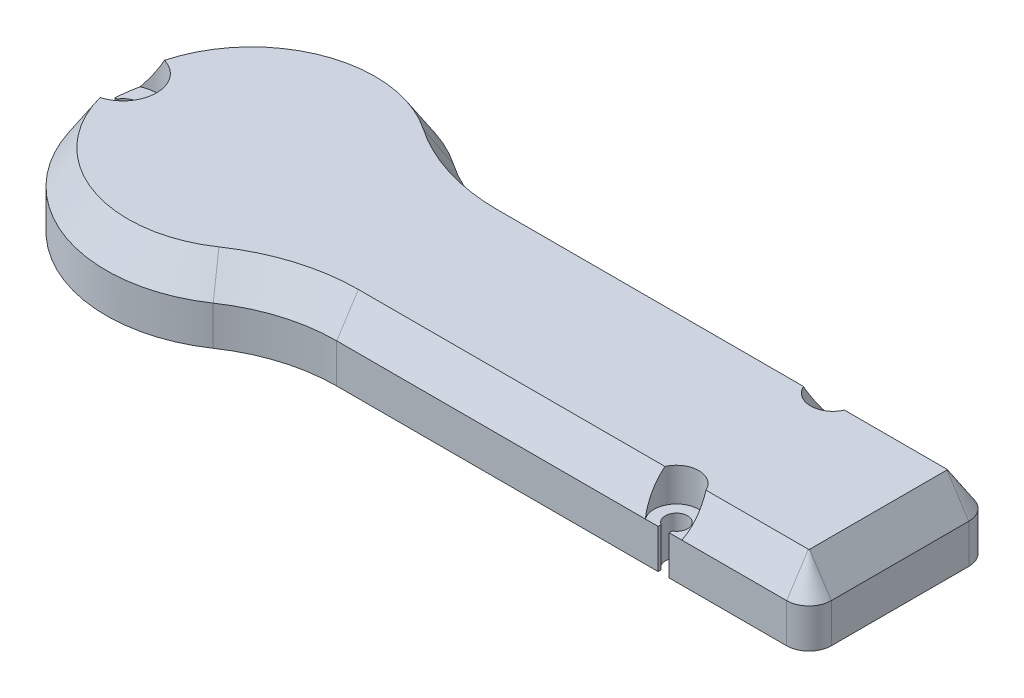
SolidWorks part; units mm, degrees
ref_plane "Front Plane" through (0, 0, 0) normal (0, 0, 1) x (1, 0, 0)
ref_plane "Top Plane" through (0, 0, 0) normal (0, 1, 0) x (1, 0, 0)
ref_plane "Right Plane" through (0, 0, 0) normal (1, 0, 0) x (0, 0, -1)
sketch "Sketch1" plane through (0, 0, 0) normal (0, 1, 0) x (1, 0, 0)
  line L0 (10.1321, 8.145) -> (10.1321, -8.145) construction
  line L1 (0, 0) -> (-11.5, 0) construction
  line L6 (0, 0) -> (45, 0) construction
  line L7 (10.1321, 8.145) -> (44.5, 8.145)
  line L9 (10.1321, -8.145) -> (44.5, -8.145)
  line L16 (58, 8.145) -> (58, -8.145)
  line L17 (45, 0) -> (45, 7) construction
  line L18 (0, 0) -> (58, 0) construction
  line L19 (45, 0) -> (45, -7) construction
  line L20 (-11.5, 0) -> (-13, 0) construction
  line L21 (-12.7, -0.75) -> (-12.7, 0.75) construction
  line L22 (45, -7) -> (45, -8.145) construction
  line L27 (45, -8.145) -> (45, 8.145) construction
  line L28 (44.5, 7.845) -> (45.5, 7.845) construction
  line L29 (44.5, -7.845) -> (45.5, -7.845) construction
  line L31 (44.5, 7.866) -> (44.5, 8.145)
  line L33 (45.5, 7.866) -> (45.5, 8.145)
  line L34 (45.5, -8.145) -> (58, -8.145)
  line L36 (44.5, -7.866) -> (44.5, -8.145)
  line L38 (45.5, -7.866) -> (45.5, -8.145)
  line L39 (45.5, 8.145) -> (58, 8.145)
  line L41 (-12.799, 0.75) -> (-12.9783, 0.75)
  line L43 (-12.799, -0.75) -> (-12.9783, -0.75)
  arc A0 (10.1321, 8.145) -> (-12.9783, 0.75) centre (0, 0) ccw
  circle A1 centre (0, 0) radius 11.5 construction
  arc A6 (-12.799, -0.75) -> (-12.799, 0.75) centre (-11.5, 0) ccw
  arc A7 (44.5, 7.866) -> (45.5, 7.866) centre (45, 7) ccw
  arc A8 (45.5, -7.866) -> (44.5, -7.866) centre (45, -7) ccw
  arc A9 (-12.9783, -0.75) -> (10.1321, -8.145) centre (0, 0) ccw
  point P19 (-12.7, 0)
  point P27 (45, 7.845)
  point P32 (45, -7.845)
  dimension "D2" = 26
  dimension "D4" = 23
  dimension "D6" = 58
  dimension "D7" = 7
  dimension "D12" = 0.3
  dimension "D13" = 0.3
  dimension "D5" = 45
  dimension "D3" = 3
  dimension "D9" = 2
  dimension "D10" = 2
  dimension "D1" = 16.29
  dimension "D8" = 7
  dimension "D11" = 0.3
extrude "Boss-Extrude1" add sketch "Sketch1" along normal blind 6.5
sketch "Sketch3" plane through (0, 0, 0) normal (0, -1, 0) x (1, 0, 0)
  circle A0 centre (0, 0) radius 8
  dimension "D1" = 16
extrude "Cut-Extrude2" cut sketch "Sketch3" against normal blind 5.5
chamfer "Chamfer4" distance 1 angle 45 2 edges at (0, 5.5, -8) (0, 0, -8)
sketch "Sketch4" plane through (0, 6.5, 0) normal (0, 1, 0) x (1, 0, 0)
  circle A1 centre (45, 7) radius 2
  circle A2 centre (45, -7) radius 2
  circle A3 centre (-11.5, 0) radius 3
  dimension "D1" = 6
  dimension "D2" = 4
  dimension "D3" = 4
fillet "Fillet3" radius 2 2 edges at (58, 3.25, -8.145) (58, 3.25, 8.145)
fillet "Fillet4" radius 15 2 edges at (10.1321, 3.25, 8.145) (10.1321, 3.25, -8.145)
chamfer "Chamfer7" distance 3 angle 33 11 edges at (-5.7441, 6.5, -11.6621) (11.3412, 6.5, -8.81) (30.1289, 6.5, -8.145) (50.75, 6.5, -8.145) (57.4142, 6.5, -7.5592) (58, 6.5, 0) (57.4142, 6.5, 7.5592) (50.75, 6.5, 8.145) (30.1289, 6.5, 8.145) (11.3412, 6.5, 8.81) (-5.7441, 6.5, 11.6621)
extrude "Cut-Extrude7" cut sketch "Sketch4" against normal blind 3
